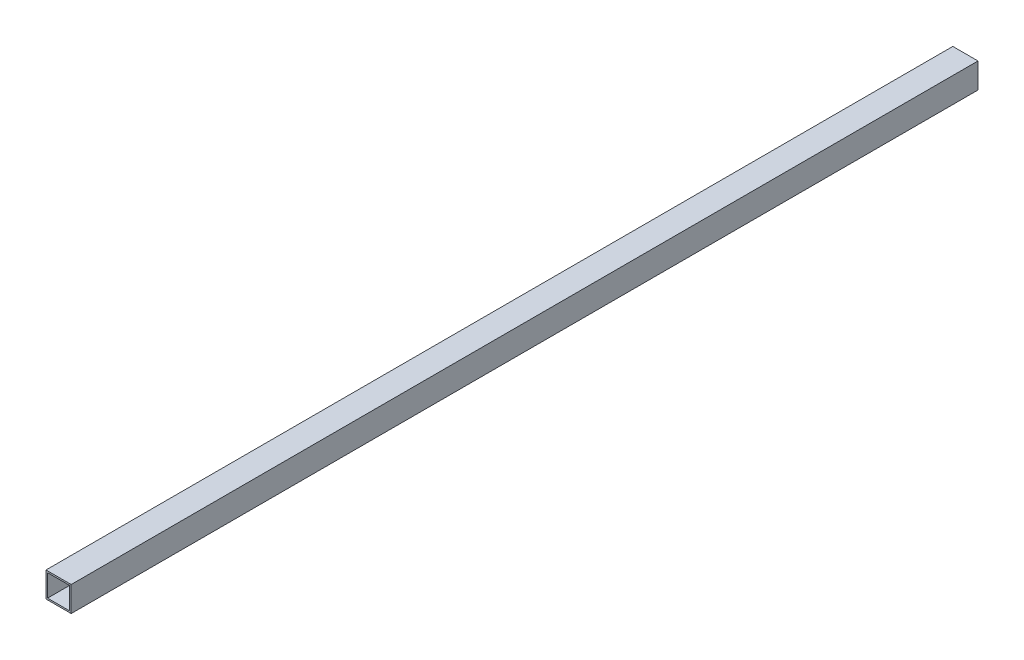
SolidWorks part; units mm, degrees
ref_plane "Front Plane" through (0, 0, 0) normal (0, 0, 1) x (1, 0, 0)
ref_plane "Top Plane" through (0, 0, 0) normal (0, 1, 0) x (1, 0, 0)
ref_plane "Right Plane" through (0, 0, 0) normal (1, 0, 0) x (0, 0, -1)
sketch "Sketch1" plane through (0, 0, 0) normal (0, 0, 1) x (1, 0, 0)
  line L1 (-12.7, 12.7) -> (12.7, 12.7)
  line L2 (-12.7, 12.7) -> (-12.7, -12.7)
  line L3 (-12.7, -12.7) -> (12.7, -12.7)
  line L4 (12.7, 12.7) -> (12.7, -12.7)
  line L5 (-12.7, 12.7) -> (12.7, -12.7) construction
  line L6 (-12.7, -12.7) -> (12.7, 12.7) construction
  line L7 (-11.1125, 11.1125) -> (11.1125, 11.1125)
  line L8 (-11.1125, 11.1125) -> (-11.1125, -11.1125)
  line L9 (-11.1125, -11.1125) -> (11.1125, -11.1125)
  line L10 (11.1125, 11.1125) -> (11.1125, -11.1125)
  line L11 (-11.1125, 11.1125) -> (11.1125, -11.1125) construction
  line L12 (-11.1125, -11.1125) -> (11.1125, 11.1125) construction
  point P0 (0, 0)
  point P6 (0, 0)
  dimension "D1" = 25.4
  dimension "D2" = 25.4
  dimension "D3" = 1.5875
  dimension "D4" = 1.5875
extrude "Boss-Extrude1" add sketch "Sketch1" along normal blind 914.4
